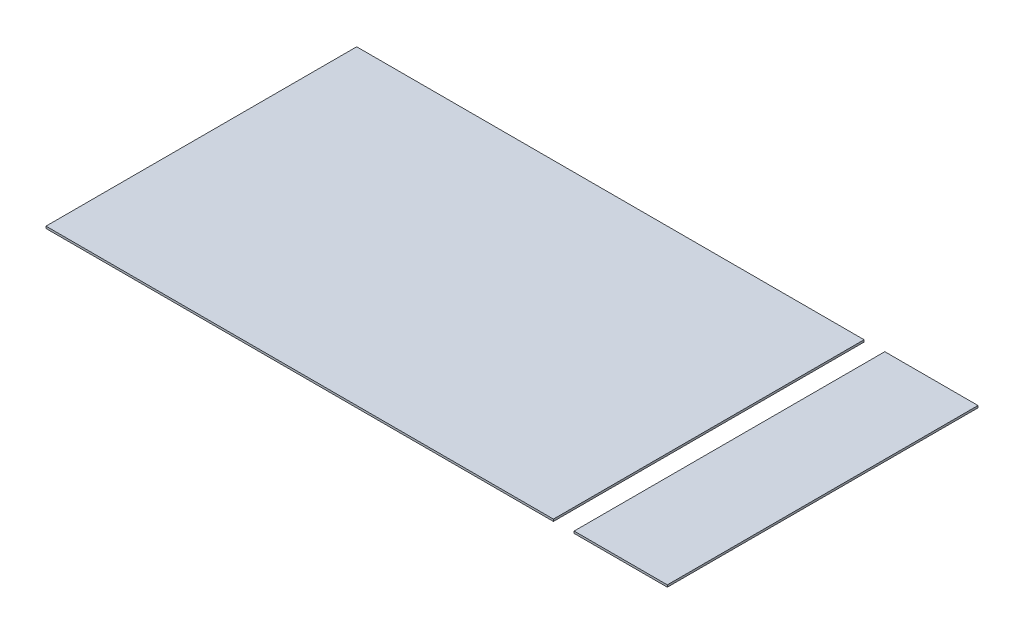
SolidWorks part; units mm, degrees
ref_plane "Front Plane" through (0, 0, 0) normal (0, 0, 1) x (1, 0, 0)
ref_plane "Top Plane" through (0, 0, 0) normal (0, 1, 0) x (1, 0, 0)
ref_plane "Right Plane" through (0, 0, 0) normal (1, 0, 0) x (0, 0, -1)
sketch "Sketch1" plane through (0, 0, 0) normal (0, 1, 0) x (1, 0, 0)
  line L1 (-8.2878, 3.8834) -> (16.2122, 3.8834)
  line L2 (-8.2878, 3.8834) -> (-8.2878, -11.1166)
  line L3 (-8.2878, -11.1166) -> (16.2122, -11.1166)
  line L4 (16.2122, 3.8834) -> (16.2122, -11.1166)
  line L5 (17.2122, -11.1166) -> (21.7122, -11.1166)
  line L6 (17.2122, -11.1166) -> (17.2122, 3.8834)
  line L7 (17.2122, 3.8834) -> (21.7122, 3.8834)
  line L8 (21.7122, -11.1166) -> (21.7122, 3.8834)
  dimension "D1" = 24.5
  dimension "D2" = 15
  dimension "D3" = 1
  dimension "D4" = 4.5
extrude "Boss-Extrude1" add sketch "Sketch1" along normal blind 0.1
